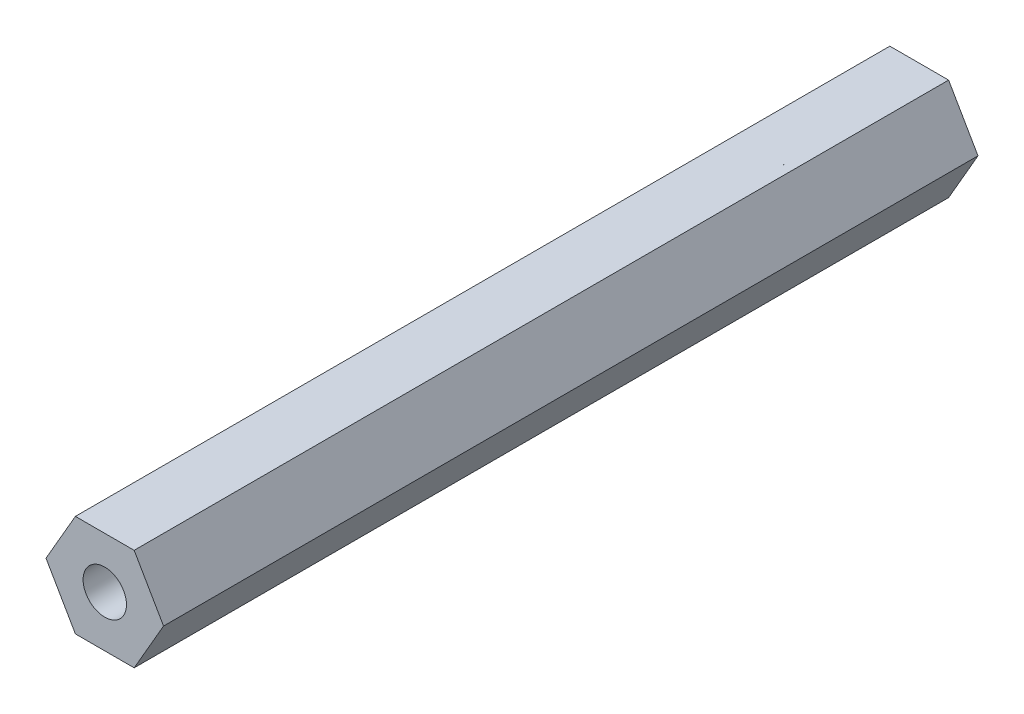
SolidWorks part; units mm, degrees
ref_plane "Front Plane" through (0, 0, 0) normal (0, 0, 1) x (1, 0, 0)
ref_plane "Top Plane" through (0, 0, 0) normal (0, 1, 0) x (1, 0, 0)
ref_plane "Right Plane" through (0, 0, 0) normal (1, 0, 0) x (0, 0, -1)
sketch "Sketch1" plane through (0, 0, 0) normal (0, 0, 1) x (1, 0, 0)
  line L1 (7.3323, 0) -> (3.6662, 6.35)
  line L2 (3.6662, 6.35) -> (-3.6662, 6.35)
  line L3 (-3.6662, 6.35) -> (-7.3323, 0)
  line L4 (-7.3323, 0) -> (-3.6662, -6.35)
  line L5 (-3.6662, -6.35) -> (3.6662, -6.35)
  line L6 (3.6662, -6.35) -> (7.3323, 0)
  circle A0 centre (0, 0) radius 6.35 construction
  dimension "D1" = 12.7
extrude "Boss-Extrude1" add sketch "Sketch1" along normal mid plane 101.6
hole_wizard "1/4-28 Tapped Hole1" positions "Sketch3" profile "Sketch2" tap size "1/4-28" standard "ANSI Inch"
sketch "Sketch3" plane through (0, 0, 50.8) normal (0, 0, 1) x (1, 0, 0)
  point P0 (0, 0)
sketch "Sketch2" plane through (0, 0, 50.8) normal (1, 0, 0) x (0, -1, 0)
  line L0 (0, 0) -> (0, 58.7754)
  line L1 (0, 58.7754) -> (2.7051, 57.15)
  line L2 (2.7051, 57.15) -> (2.7051, 0)
  line L5 (2.7051, 0) -> (0, 0)
  line L10 (0, 58.7754) -> (-2.7051, 57.15) construction
  line L11 (0, -6.35) -> (0, 107.95) construction
  dimension "Tap Drill Dia." = 5.4102
  dimension "Tap Drill Depth" = 57.15
  dimension "Drill Angle" = 118
hole_wizard "1/4-28 Tapped Hole2" positions "Sketch5" profile "Sketch4" tap size "1/4-28" standard "ANSI Inch"
sketch "Sketch5" plane through (0, 0, -50.8) normal (0, 0, -1) x (-1, 0, 0)
  point P0 (0, 0)
sketch "Sketch4" plane through (0, 0, -50.8) normal (1, 0, 0) x (0, 1, 0)
  line L0 (0, 0) -> (0, 58.7754)
  line L1 (0, 58.7754) -> (2.7051, 57.15)
  line L2 (2.7051, 57.15) -> (2.7051, 0)
  line L5 (2.7051, 0) -> (0, 0)
  line L10 (0, 58.7754) -> (-2.7051, 57.15) construction
  line L11 (0, -6.35) -> (0, 107.95) construction
  dimension "Tap Drill Dia." = 5.4102
  dimension "Tap Drill Depth" = 57.15
  dimension "Drill Angle" = 118
